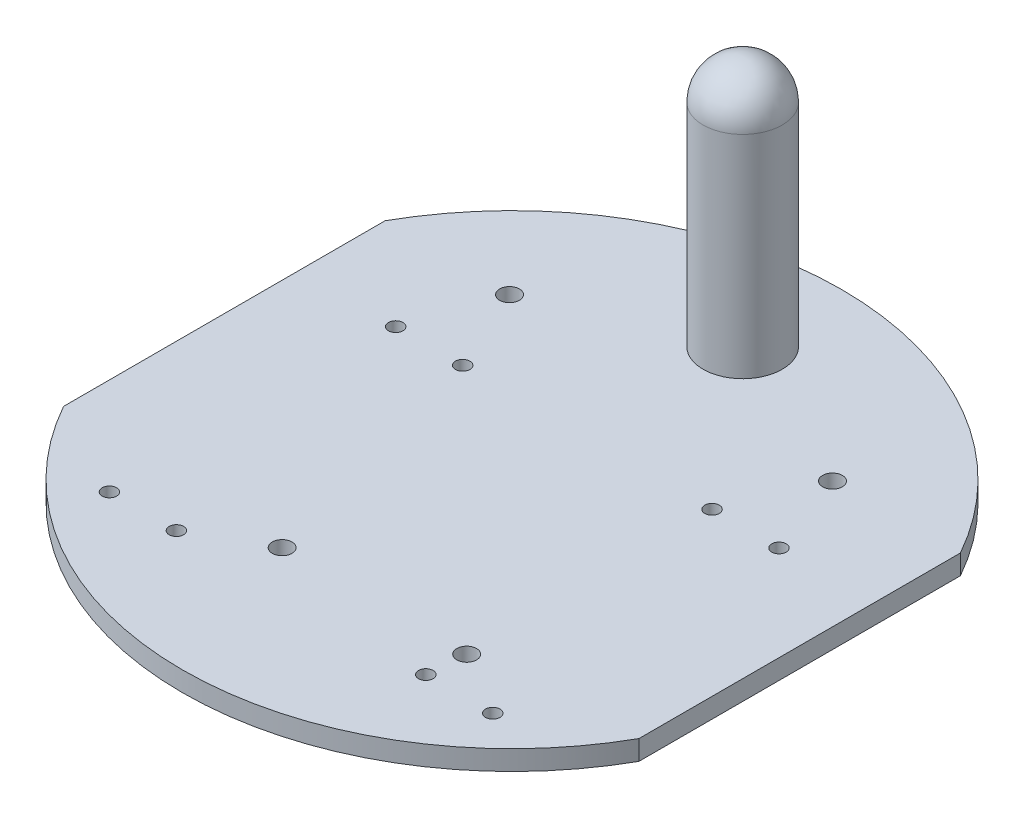
SolidWorks part; units mm, degrees
ref_plane "Front Plane" through (0, 0, 0) normal (0, 0, 1) x (1, 0, 0)
ref_plane "Top Plane" through (0, 0, 0) normal (0, 1, 0) x (1, 0, 0)
ref_plane "Right Plane" through (0, 0, 0) normal (1, 0, 0) x (0, 0, -1)
sketch "Sketch2" plane through (0, 0, 0) normal (0, 1, 0) x (1, 0, 0)
  circle A0 centre (0, 0) radius 50
  dimension "D1" = 100
extrude "Boss-Extrude1" add sketch "Sketch2" along normal blind 3
sketch "Sketch3" plane through (0, 3, 0) normal (0, 1, 0) x (1, 0, 0)
  line L0 (0, 0) -> (0, 50) construction
  circle A0 centre (0, 0) radius 50 construction
  circle A1 centre (0, 35) radius 6
  dimension "D2" = 12
  dimension "D1" = 15
extrude "Boss-Extrude2" add sketch "Sketch3" along normal blind 38.1
fillet "Fillet1" radius 6 1 edges at (0, 41.1, -29)
sketch "Sketch6" plane through (0, 3, 0) normal (0, 1, 0) x (1, 0, 0)
  line L0 (0, 0) -> (-50, 0) construction
  line L1 (-43.65, 0) -> (-43.65, 24.386) construction
  line L2 (0, 0) -> (50, 0) construction
  line L3 (43.65, 24.386) -> (43.65, 0) construction
  line L4 (-43.65, 24.386) -> (-43.65, -24.386)
  line L5 (43.65, 24.386) -> (43.65, -24.386)
  line L6 (-43.65, 24.386) -> (-50, 24.386)
  line L7 (-50, 24.386) -> (-50, 0)
  line L8 (-50, 0) -> (-50, -24.386)
  line L9 (-50, -24.386) -> (-43.65, -24.386)
  line L10 (43.65, -24.386) -> (50, -24.386)
  line L11 (50, -24.386) -> (50, 0)
  line L12 (50, 0) -> (50, 24.386)
  line L13 (50, 24.386) -> (43.65, 24.386)
  circle A0 centre (0, 0) radius 50 construction
  dimension "D1" = 6.35
  dimension "D2" = 6.35
extrude "Cut-Extrude1" cut sketch "Sketch6" against normal blind 38.1
sketch "Sketch7" plane through (0, 3, 0) normal (0, 1, 0) x (1, 0, 0)
  line L1 (-28.93, 11.281) -> (29.23, 11.281)
  line L2 (-28.93, 11.281) -> (-28.93, -32.153)
  line L3 (-28.93, -32.153) -> (29.23, -32.153)
  line L4 (29.23, 11.281) -> (29.23, -32.153)
  line L5 (19.07, 11.281) -> (-18.77, 11.281)
  line L6 (19.07, 11.281) -> (19.07, -32.153)
  line L7 (19.07, -32.153) -> (-18.77, -32.153)
  line L8 (-18.77, 11.281) -> (-18.77, -32.153)
  circle A0 centre (-28.93, 11.281) radius 1.1
  circle A1 centre (-18.77, 11.281) radius 1.1
  circle A2 centre (19.07, 11.281) radius 1.1
  circle A3 centre (29.23, 11.281) radius 1.1
  circle A4 centre (29.23, -32.153) radius 1.1
  circle A5 centre (19.07, -32.153) radius 1.1
  circle A6 centre (-18.77, -32.153) radius 1.1
  circle A7 centre (-28.93, -32.153) radius 1.1
  dimension "D1" = 2.2
  dimension "D2" = 2.2
  dimension "D3" = 2.2
  dimension "D4" = 2.2
  dimension "D5" = 2.2
  dimension "D6" = 2.2
  dimension "D7" = 2.2
  dimension "D8" = 2.2
extrude "Cut-Extrude2" cut sketch "Sketch7" against normal blind 2.2 contours A0 | A1 | A2 | A3 | A4 | A5 | A6 | A7
sketch "Sketch8" plane through (0, 0, 0) normal (0, -1, 0) x (-1, 0, 0)
  circle A0 centre (-19.5, -26.374) radius 1.5
  circle A1 centre (8.5, -26.374) radius 1.5
  circle A2 centre (-24.5, 24.126) radius 1.5
  circle A3 centre (24.5, 24.126) radius 1.5
  dimension "D1" = 3
  dimension "D2" = 3
  dimension "D3" = 3
  dimension "D4" = 3
extrude "Cut-Extrude3" cut sketch "Sketch8" against normal up to surface (3 mm away) up to face at (-18.77, 3, -10.181)
equation "\"2.2mmmm\"=10"
